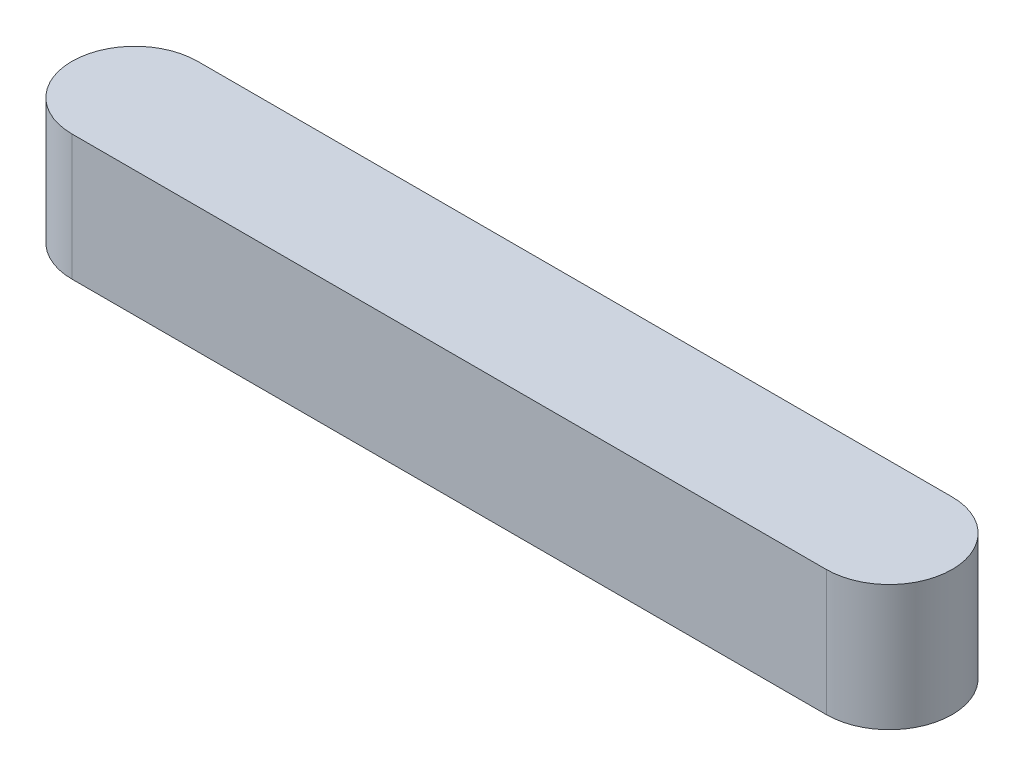
SolidWorks part; units mm, degrees
ref_plane "Front Plane" through (0, 0, 0) normal (0, 0, 1) x (1, 0, 0)
ref_plane "Top Plane" through (0, 0, 0) normal (0, 1, 0) x (1, 0, 0)
ref_plane "Right Plane" through (0, 0, 0) normal (1, 0, 0) x (0, 0, -1)
sketch "Sketch3" plane through (0, 0, 0) normal (0, 1, 0) x (1, 0, 0)
  line L0 (-60, 0) -> (60, 0) construction
  line L1 (-60, 10) -> (60, 10)
  line L2 (-60, -10) -> (60, -10)
  arc A0 (-60, 10) -> (-60, -10) centre (-60, 0) ccw
  arc A1 (60, -10) -> (60, 10) centre (60, 0) ccw
  point P3 (0, 0)
  point P10 (35, 0)
  dimension "D1" = 10
  dimension "D2" = 120
  dimension "D3" = 25
extrude "Boss-Extrude1" add sketch "Sketch3" along normal blind 20 contours L1 A1 L2 A0
